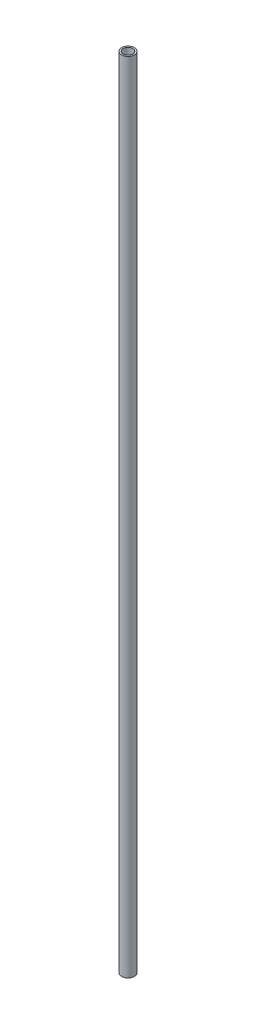
SolidWorks part; units mm, degrees
material "Thornel Mat VMA"
ref_plane "前视基准面" through (0, 0, 0) normal (0, 0, 1) x (1, 0, 0)
ref_plane "上视基准面" through (0, 0, 0) normal (0, 1, 0) x (1, 0, 0)
ref_plane "右视基准面" through (0, 0, 0) normal (1, 0, 0) x (0, 0, -1)
sketch "草图1" plane through (0, 0, 0) normal (0, 1, 0) x (1, 0, 0)
  circle A0 centre (0, 0) radius 1.5
  circle A1 centre (0, 0) radius 2
  dimension "D1" = 4
  dimension "D2" = 3
extrude "凸台-拉伸1" add sketch "草图1" along normal blind 250
